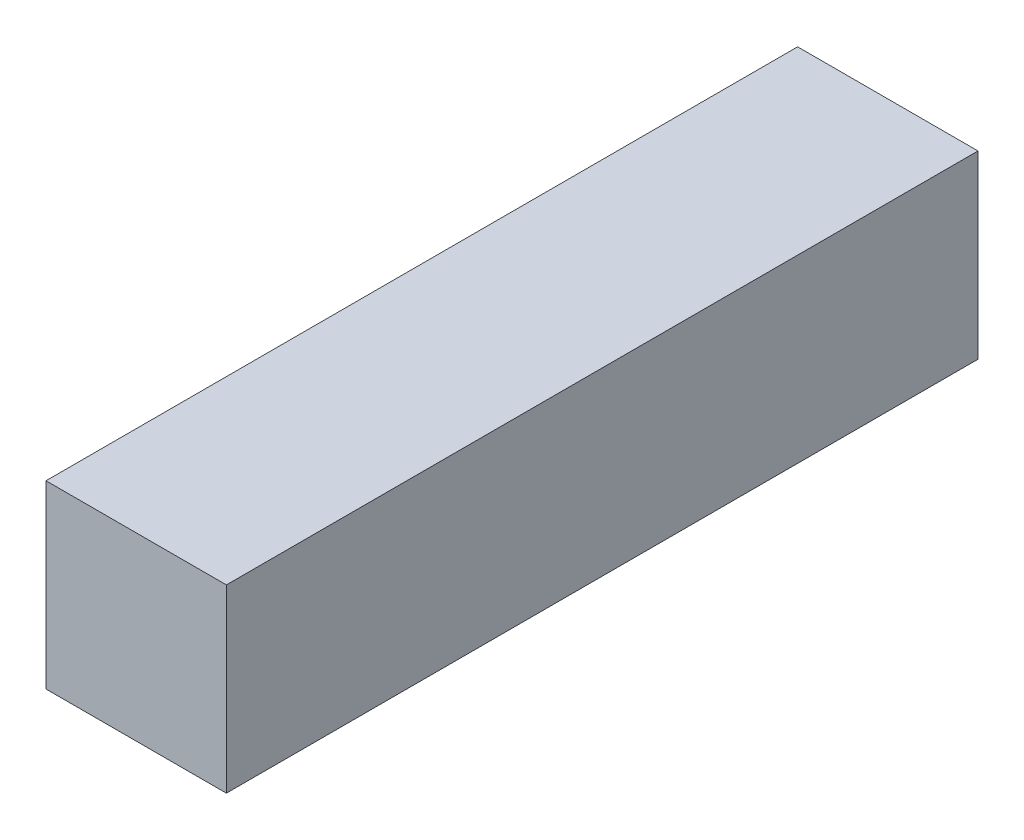
SolidWorks part; units mm, degrees
ref_plane "Front Plane" through (0, 0, 0) normal (0, 0, 1) x (1, 0, 0)
ref_plane "Top Plane" through (0, 0, 0) normal (0, 1, 0) x (1, 0, 0)
ref_plane "Right Plane" through (0, 0, 0) normal (1, 0, 0) x (0, 0, -1)
sketch "Sketch1" plane through (0, 0, 0) normal (0, 0, 1) x (1, 0, 0)
  line L1 (76.2, 76.2) -> (-76.2, 76.2)
  line L2 (76.2, 76.2) -> (76.2, -76.2)
  line L3 (76.2, -76.2) -> (-76.2, -76.2)
  line L4 (-76.2, 76.2) -> (-76.2, -76.2)
  line L5 (76.2, 76.2) -> (-76.2, -76.2) construction
  line L6 (76.2, -76.2) -> (-76.2, 76.2) construction
  point P0 (0, 0)
  dimension "D1" = 152.4
  dimension "D2" = 152.4
extrude "Boss-Extrude1" add sketch "Sketch1" along normal blind 635
